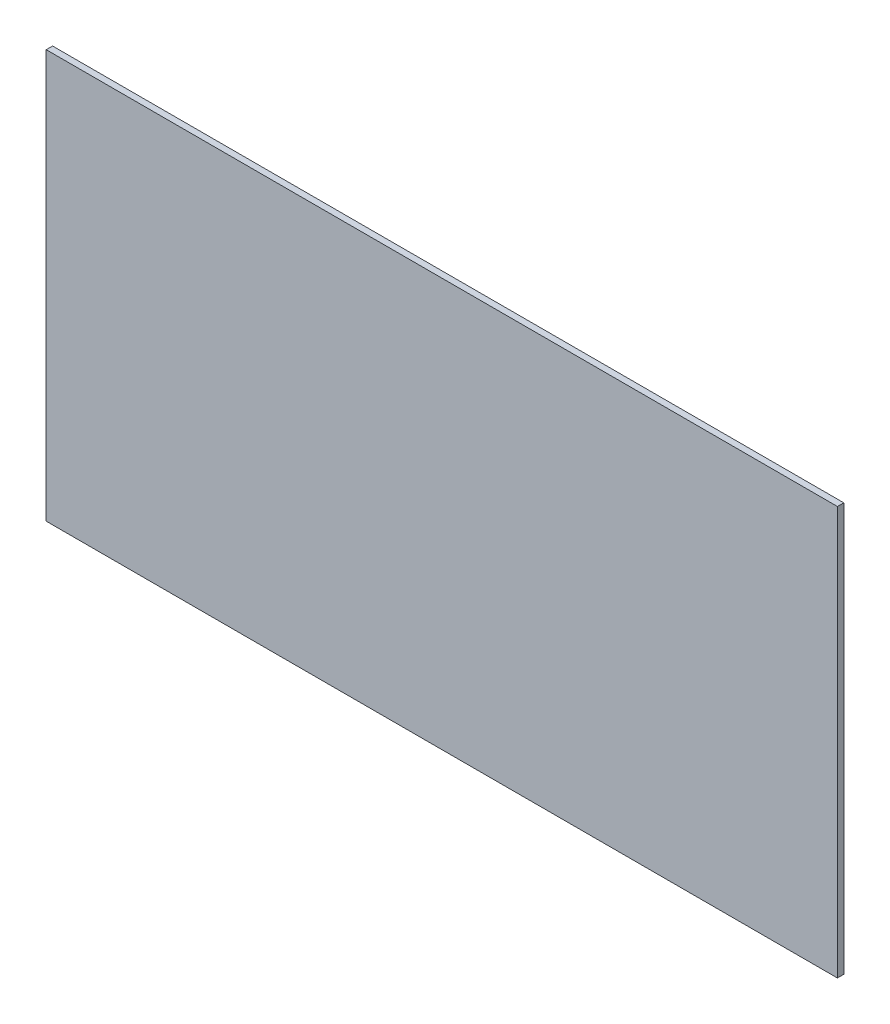
SolidWorks part; units mm, degrees
material "ABS PC"
ref_plane "Front Plane" through (0, 0, 0) normal (0, 0, 1) x (1, 0, 0)
ref_plane "Top Plane" through (0, 0, 0) normal (0, 1, 0) x (1, 0, 0)
ref_plane "Right Plane" through (0, 0, 0) normal (1, 0, 0) x (0, 0, -1)
sketch "Sketch1" plane through (0, 0, 0) normal (0, 0, 1) x (1, 0, 0)
  line L1 (-196.85, -101.6) -> (196.85, -101.6)
  line L2 (-196.85, -101.6) -> (-196.85, 101.6)
  line L3 (-196.85, 101.6) -> (196.85, 101.6)
  line L4 (196.85, -101.6) -> (196.85, 101.6)
  line L5 (0, 101.6) -> (0, -101.6) construction
  line L6 (-196.85, 0) -> (196.85, 0) construction
  point P0 (0, 0)
  point P4 (-137.795, 0)
  point P5 (137.795, 0)
  point P6 (0, 71.12)
  point P7 (0, -71.12)
  dimension "Length" = 393.7
  dimension "Width" = 203.2
  dimension "Break" = 59.055
  dimension "D2" = 59.055
  dimension "D1" = 30.48
  dimension "D3" = 30.48
sketch "Sketch2" plane through (0, 0, 0) normal (1, 0, 0) x (0, 0, -1)
  line L0 (-1.5875, -101.6) -> (1.5875, -101.6)
  dimension "Thickness" = 3.175
sketch "Sketch3" plane through (0, 0, 0) normal (0, 0, 1) x (1, 0, 0)
  line L0 (-196.85, -101.6) -> (-196.85, 101.6) construction
  line L1 (-196.85, -101.6) -> (196.85, -101.6) construction
  line L2 (196.85, -101.6) -> (196.85, 101.6) construction
  line L3 (-196.85, 101.6) -> (196.85, 101.6) construction
  line L4 (-196.85, -101.6) -> (-196.85, 101.6)
  line L5 (-196.85, -101.6) -> (196.85, -101.6)
  line L6 (196.85, -101.6) -> (196.85, 101.6)
  line L7 (-196.85, 101.6) -> (196.85, 101.6)
extrude "Boss-Extrude1" add sketch "Sketch3" along normal mid plane 3.175
equation "\"D1@Boss-Extrude1\"=\"thickness@sketch2\""
equation "\"Break@Sketch1\" = \"Length@Sketch1\" * 0.15"
equation "\"D2@Sketch1\" = \"Break@Sketch1\""
equation "\"D1@Sketch1\"=\"Width@Sketch1\"*0.15"
equation "\"D3@Sketch1\"=\"D1@Sketch1\""
